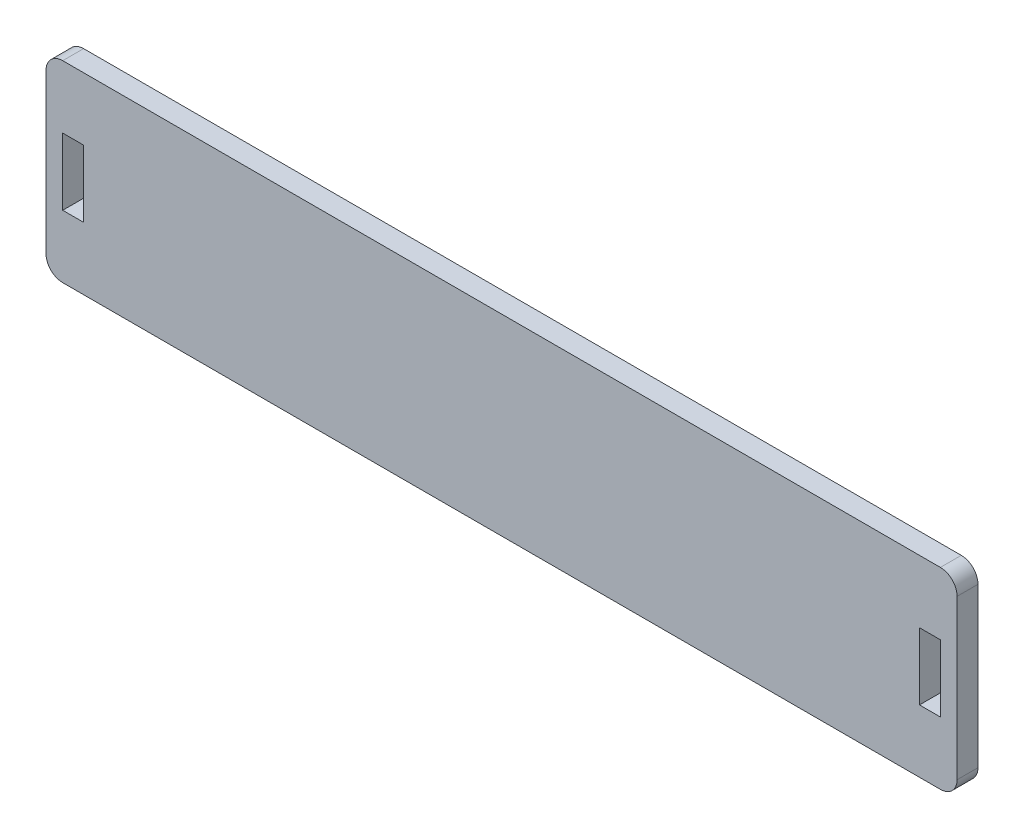
SolidWorks part; units mm, degrees
material "Beech"
ref_plane "Front" through (0, 0, 0) normal (0, 0, 1) x (1, 0, 0)
ref_plane "Top" through (0, 0, 0) normal (0, 1, 0) x (1, 0, 0)
ref_plane "Right" through (0, 0, 0) normal (1, 0, 0) x (0, 0, -1)
sketch "Sketch1" plane through (0, 0, 0) normal (0, 0, 1) x (1, 0, 0)
  line L0 (0, -5.6139) -> (0, 7.3412) construction
  line L1 (-54.5, -11.5) -> (54.5, -11.5)
  line L2 (-54.5, -11.5) -> (-54.5, 11.5)
  line L3 (-54.5, 11.5) -> (54.5, 11.5)
  line L4 (54.5, -11.5) -> (54.5, 11.5)
  line L5 (-54.5, -11.5) -> (54.5, 11.5) construction
  line L6 (-54.5, 11.5) -> (54.5, -11.5) construction
  line L7 (50, -4) -> (52.5, -4)
  line L8 (50, -4) -> (50, 4)
  line L9 (50, 4) -> (52.5, 4)
  line L10 (52.5, -4) -> (52.5, 4)
  line L11 (50, -4) -> (52.5, 4) construction
  line L12 (50, 4) -> (52.5, -4) construction
  line L13 (-50, 4) -> (-52.5, 4)
  line L14 (-52.5, -4) -> (-52.5, 4)
  line L15 (-50, -4) -> (-52.5, -4)
  line L16 (-50, -4) -> (-50, 4)
  point P0 (0, 0)
  point P6 (51.25, 0)
  point P13 (54.5, 0)
  dimension "D1" = 109
  dimension "D2" = 2
  dimension "D3" = 2.5
  dimension "D4" = 8
  dimension "D5" = 23
extrude "Boss-Extrude1" add sketch "Sketch1" along normal blind 2.5
fillet "Fillet1" radius 2
sketch "Sketch2" plane through (0, 0, 0) normal (0, 0, -1) x (-1, 0, 0)
  line L0 (-12.5, 1.5) -> (12.5, 1.5) construction
  line L1 (12.5, -2.5) -> (-12.5, -2.5) construction
  line L2 (-52.5, 11.5) -> (52.5, 11.5) construction
  text T0 "OPPOSITE\r\n" font "Century Gothic" height 3
  text T1 "Made In Egypt" font "Century Gothic" height 1.75
  point P7 (0, 1.5)
  point P8 (0, 11.5)
  dimension "D1" = 4
  dimension "D2" = 10
  dimension "D3" = 25
extrude "Cut-Extrude1" cut sketch "Sketch2" against normal blind 1
